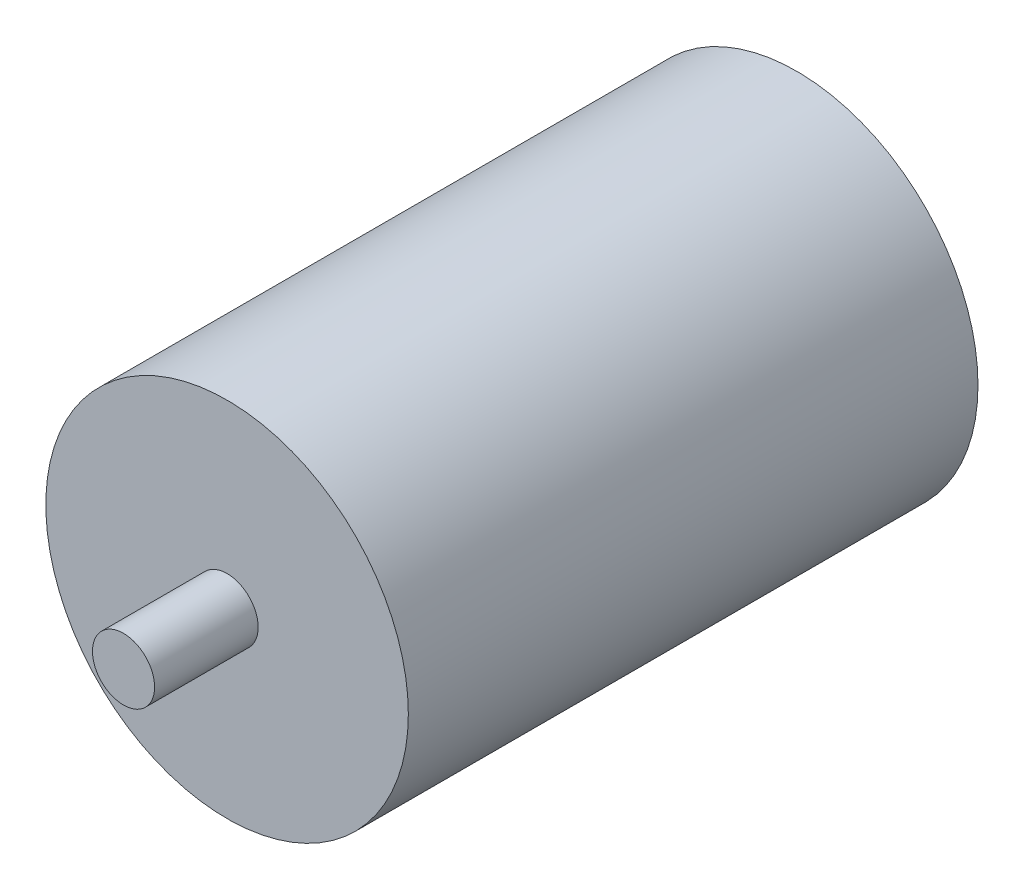
SolidWorks part; units mm, degrees
ref_plane "Front Plane" through (0, 0, 0) normal (0, 0, 1) x (1, 0, 0)
ref_plane "Top Plane" through (0, 0, 0) normal (0, 1, 0) x (1, 0, 0)
ref_plane "Right Plane" through (0, 0, 0) normal (1, 0, 0) x (0, 0, -1)
sketch "Sketch1" plane through (0, 0, 0) normal (0, 0, 1) x (1, 0, 0)
  circle A0 centre (0, 0) radius 38.1
  circle A1 centre (0, 0) radius 44.45
  dimension "D1" = 76.2
  dimension "D2" = 88.9
extrude "Boss-Extrude1" add sketch "Sketch1" along normal blind 127
sketch "Sketch2" plane through (0, 0, 127) normal (0, 0, 1) x (1, 0, 0)
  circle A0 centre (0, 0) radius 44.45 construction
  circle A1 centre (0, 0) radius 44.45
extrude "Boss-Extrude2" add sketch "Sketch2" along normal blind 12.7
sketch "Sketch3" plane through (0, 0, 139.7) normal (0, 0, 1) x (1, 0, 0)
  circle A0 centre (0, 0) radius 7.62
  dimension "D1" = 15.24
extrude "Boss-Extrude3" add sketch "Sketch3" along normal blind 25.4
